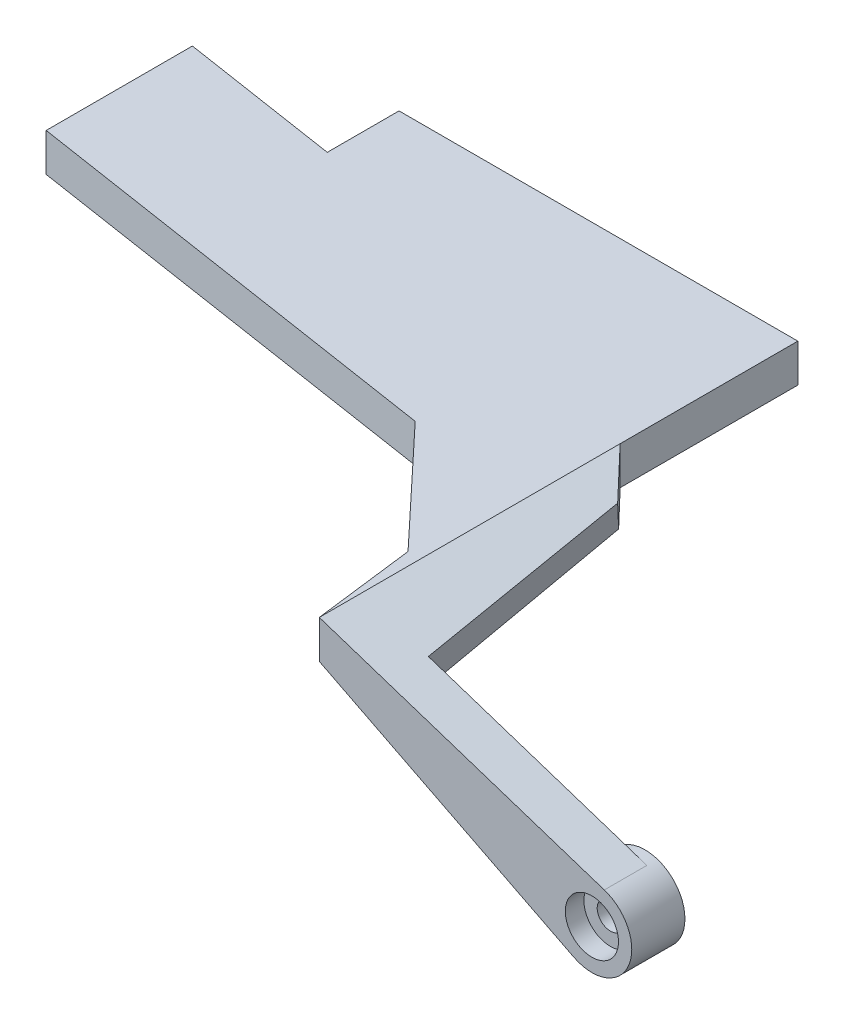
SolidWorks part; units mm, degrees
ref_plane "Alzado" through (0, 0, 0) normal (0, 0, 1) x (1, 0, 0)
ref_plane "Planta" through (0, 0, 0) normal (0, 1, 0) x (1, 0, 0)
ref_plane "Vista lateral" through (0, 0, 0) normal (1, 0, 0) x (0, 0, -1)
sketch "Croquis1" plane through (0, 0, 0) normal (0, 0, 1) x (1, 0, 0)
  circle A1 centre (10, 0) radius 2.5
  circle A2 centre (10, 0) radius 5
  circle A3 centre (10, 0) radius 6
extrude "Saliente-Extruir1" add sketch "Croquis1" along normal blind 10 contours A3 A2 | A2 A1 | A1
sketch "Croquis2" plane through (0, 0, 10) normal (0, 0, 1) x (1, 0, 0)
  circle A0 centre (10, 0) radius 2.5
  circle A1 centre (10, 0) radius 5
extrude "Saliente-Extruir2" add sketch "Croquis2" against normal blind 7
sketch "Croquis3" plane through (0, 0, 10) normal (0, 0, 1) x (1, 0, 0)
  circle A0 centre (10, 0) radius 5
  dimension "D1" = 10
extrude "Cortar-Extruir2" cut sketch "Croquis3" against normal up to vertex (3.5 mm away)
sketch "Croquis4" plane through (0, 0, 0) normal (0, 0, -1) x (-1, 0, 0)
  circle A0 centre (-10, 0) radius 6
extrude "Cortar-Extruir3" cut sketch "Croquis4" against normal up to vertex (0.8 mm away)
sketch "Croquis5" plane through (0, 0, 10) normal (0, 0, 1) x (1, 0, 0)
  circle A0 centre (10, 0) radius 7.5
  circle A1 centre (10, 0) radius 5
  dimension "D1" = 15
  dimension "D2" = 10
extrude "Saliente-Extruir3" add sketch "Croquis5" against normal up to vertex (10 mm away)
sketch "Croquis6" plane through (0, 0, 10) normal (0, 0, 1) x (1, 0, 0)
  line L0 (-41.2676, -17.5483) -> (6.6124, 6.6914)
  line L1 (-41.2676, -24.7171) -> (12.3385, -7.1261)
  line L2 (-41.2676, -17.5483) -> (-41.2676, -24.7171)
  circle A0 centre (10, 0) radius 7.5 construction
  arc A1 (6.6124, 6.6914) -> (12.3385, -7.1261) centre (10, 0) ccw
extrude "Saliente-Extruir4" add sketch "Croquis6" against normal blind 8
sketch "Croquis7" plane through (0, 0, 10) normal (0, 0, 1) x (1, 0, 0)
  line L0 (-41.2676, -24.7171) -> (-116.2676, -24.7171)
  line L1 (-41.2676, -24.7171) -> (-41.2676, -17.5483)
  line L4 (-41.2676, -17.5483) -> (-116.2676, -17.5483)
  line L5 (-116.2676, -17.5483) -> (-116.2676, -24.7171)
  dimension "D1" = 75
extrude "Saliente-Extruir5" add sketch "Croquis7" against normal blind 90 contours L5 L0 L1 L4
sketch "Croquis8" plane through (0, -24.7171, 0) normal (0, -1, 0) x (1, 0, 0)
  line L0 (-27.9791, 2) -> (-41.2676, -39)
  line L1 (-41.2676, 2) -> (12.3385, 2) construction
  line L2 (-41.2676, -80) -> (-41.2676, 2) construction
  line L3 (-41.2676, -39) -> (-41.2676, 2)
  line L4 (-41.2676, 2) -> (-27.9791, 2)
extrude "Saliente-Extruir6" add sketch "Croquis8" against normal up to vertex
sketch "Croquis10" plane through (0, 0, 2) normal (0, 0, -1) x (-1, 0, 0)
  line L0 (41.2676, -17.5483) -> (27.9791, -17.5483)
  line L1 (27.9791, -17.5483) -> (27.9791, -10.8209)
  line L2 (-6.6124, 6.6914) -> (41.2676, -17.5483) construction
  line L3 (27.9791, -10.8209) -> (41.2676, -17.5483)
extrude "Saliente-Extruir9" add sketch "Croquis10" along normal up to vertex (41 mm away)
sketch "Croquis11" plane through (0, 0, -39) normal (0, 0, -1) x (-1, 0, 0)
  line L0 (41.2676, -17.5483) -> (41.2676, -24.7171)
  line L1 (41.2676, -24.7171) -> (27.9791, -20.3564)
  line L2 (27.9791, -20.3564) -> (27.9791, -17.5483)
  line L3 (27.9791, -17.5483) -> (41.2676, -17.5483)
extrude "Saliente-Extruir10" add sketch "Croquis11" against normal up to vertex (49 mm away)
sketch "Croquis12" plane through (0, 0, 2) normal (0, 0, 1) x (1, 0, 0)
  line L0 (-41.2676, -24.7171) -> (-27.9791, -20.3564)
  line L1 (-27.9791, -20.3564) -> (-27.9791, -24.7171)
  line L2 (-27.9791, -24.7171) -> (-41.2676, -24.7171)
extrude "Cortar-Extruir4" cut sketch "Croquis12" against normal up to vertex
sketch "Croquis13" plane through (-1.3475, 2.6616, 0) normal (-0.4517, 0.8922, 0) x (0.8922, 0.4517, 0)
  line L0 (-29.8501, -2) -> (-37.2972, 39)
  line L1 (-44.7444, 39) -> (-29.8501, 39) construction
  line L2 (-37.2972, 39) -> (-29.8501, 39)
  line L3 (-29.8501, 39) -> (-29.8501, -2)
extrude "Cortar-Extruir5" cut sketch "Croquis13" against normal through all
sketch "Croquis14" plane through (3.3106, -10.0886, 0) normal (0.3118, -0.9501, 0) x (0.9501, 0.3118, 0)
  line L0 (-29.9583, 2) -> (-32.9314, 2)
  line L1 (-32.9314, 2) -> (-36.108, -39)
  line L2 (-36.108, -39) -> (-29.9583, 2)
extrude "Cortar-Extruir7" cut sketch "Croquis14" against normal through all contours L2 L0 L1
sketch "Croquis15" plane through (3.3106, -10.0886, 0) normal (0.3118, -0.9501, 0) x (0.9501, 0.3118, 0)
  line L0 (-26.1664, 2) -> (-33.7454, 2)
  line L1 (-32.9314, 2) -> (9.5015, 2) construction
  line L2 (-33.7454, 2) -> (-39.4297, -39)
  line L3 (-36.108, -39) -> (-46.917, -39) construction
  line L4 (-39.4297, -39) -> (-33.7454, -39)
  line L5 (-33.7454, -39) -> (-26.1664, 2)
extrude "Cortar-Extruir8" cut sketch "Croquis15" against normal through all
sketch "Croquis16" plane through (0, -17.5483, 0) normal (0, 1, 0) x (1, 0, 0)
  line L0 (-41.2676, -10) -> (-46.0414, 28.1515)
  line L1 (-46.0414, 28.1515) -> (-116.2676, 39)
  line L2 (-116.2676, 80) -> (-116.2676, -10) construction
  line L3 (-116.2676, 39) -> (-116.2676, -10)
  line L4 (-116.2676, -10) -> (-41.2676, -10)
extrude "Cortar-Extruir9" cut sketch "Croquis16" against normal through all
sketch "Croquis17" plane through (0, -24.7171, 0) normal (0, -1, 0) x (1, 0, 0)
  line L0 (-116.2676, -39) -> (-116.2676, -59.5)
  line L2 (-116.2676, -80) -> (-116.2676, -39) construction
  line L3 (-116.2676, -59.5) -> (-146.2676, -59.5)
  line L4 (-146.2676, -59.5) -> (-146.2676, -39)
  line L5 (-146.2676, -39) -> (-116.2676, -39)
  dimension "D1" = 20.5
  dimension "D2" = 30
extrude "Saliente-Extruir12" add sketch "Croquis17" against normal up to vertex
sketch "Croquis18" plane through (0, -24.7171, 0) normal (0, -1, 0) x (1, 0, 0)
  line L0 (-146.2676, -59.5) -> (-116.2676, -59.5)
  line L1 (-116.2676, -59.5) -> (-146.2676, -64.1442)
  line L2 (-146.2676, -64.1442) -> (-146.2676, -59.5)
  line L4 (-116.2676, -39) -> (-146.2676, -43.6344)
  line L5 (-146.2676, -39) -> (-146.2676, -59.5) construction
  line L6 (-146.2676, -43.6344) -> (-146.2676, -39)
  line L7 (-146.2676, -39) -> (-116.2676, -39)
  dimension "D1" = 8.8
extrude "Cortar-Extruir10" cut sketch "Croquis18" against normal through all contours L2 L0 L1 | L7 L4 L6
sketch "Croquis19" plane through (0, -24.7171, 0) normal (0, -1, 0) x (1, 0, 0)
  line L0 (-146.2676, -59.5) -> (-116.2676, -59.5)
  line L1 (-116.2676, -59.5) -> (-146.2676, -64.1344)
  line L2 (-146.2676, -64.1344) -> (-146.2676, -59.5)
extrude "Saliente-Extruir13" add sketch "Croquis19" against normal up to vertex
sketch "Croquis20" plane through (0, -24.7171, 0) normal (0, -1, 0) x (1, 0, 0)
  line L0 (-146.2676, -64.1344) -> (-116.2676, -59.5)
  line L1 (-116.2676, -59.5) -> (-116.2676, -66.5)
  line L2 (-116.2676, -80) -> (-116.2676, -59.5) construction
  line L3 (-146.2676, -64.1344) -> (-146.2676, -71.1344)
  line L4 (-146.2676, -71.1344) -> (-116.2676, -66.5)
  dimension "D2" = 7
  dimension "D1" = 7
extrude "Saliente-Extruir14" add sketch "Croquis20" against normal up to vertex
mirror "Simetría5" about plane through (-41.2676, -24.7171, -80) normal (0, 1, 0) of bodies 122
sketch "Croquis22" plane through (3.1743, 0, -20.5486) normal (-0.1527, 0, 0.9883) x (0.9883, 0, 0.1527)
  line L0 (-151.2146, -24.7171) -> (-160.9294, -24.7171)
  line L1 (-151.2146, -31.8858) -> (-151.2146, -17.5483) construction
  line L2 (-160.9294, -24.7171) -> (-160.9294, 29.1518)
  line L3 (-160.9294, 29.1518) -> (25.9068, 29.1518)
  line L4 (25.9068, 29.1518) -> (25.9068, -24.7171)
  line L5 (25.9068, -24.7171) -> (-151.2146, -24.7171)
extrude "Cortar-Extruir12" cut sketch "Croquis22" against normal through all and the other way through all
sketch "Croquis25" plane through (0, -31.8858, 0) normal (0, -1, 0) x (1, 0, 0)
  line L2 (-41.2676, 10) -> (-46.0414, -28.1515) construction
  line L3 (-43.6545, -9.0757) -> (-64.1814, -30.9537)
  line L4 (-46.0414, -28.1515) -> (-146.2676, -43.6344) construction
  line L5 (-64.1814, -30.9537) -> (-46.0414, -28.1515)
  line L6 (-46.0414, -28.1515) -> (-43.6545, -9.0757)
  dimension "D2" = 30
extrude "Saliente-Extruir15" add sketch "Croquis25" against normal up to vertex
sketch "Croquis26" plane through (0, -31.8858, 0) normal (0, -1, 0) x (1, 0, 0)
  line L0 (-34.1535, -39) -> (-41.2676, -46.5823)
  line L1 (-41.2676, -80) -> (-41.2676, -39) construction
  line L2 (-41.2676, -46.5823) -> (-41.2676, -39)
  line L3 (-41.2676, -39) -> (-34.1535, -39)
extrude "Saliente-Extruir16" add sketch "Croquis26" against normal up to vertex
sketch "Croquis27" plane through (0, -31.8858, 0) normal (0, -1, 0) x (1, 0, 0)
  line L0 (-41.2676, -39) -> (-34.1535, -39)
  line L1 (-34.1535, -39) -> (-41.2676, -46.5823)
  line L2 (-41.2676, -46.5823) -> (-41.2676, -39)
extrude "Saliente-Extruir17" add sketch "Croquis27" along normal up to vertex
sketch "Croquis28" plane through (0, 0, -39) normal (0, 0, 1) x (1, 0, 0)
  line L0 (-41.2676, -31.8858) -> (-41.2676, -34.2856)
  line L1 (-41.2676, -34.2856) -> (-36.5274, -34.2856)
  line L2 (-36.5274, -34.2856) -> (-41.2676, -31.8858)
  line L3 (-41.2676, -24.7171) -> (-34.1535, -24.7171)
  line L4 (-34.1535, -24.7171) -> (-34.1535, -27.0516)
  line L5 (-34.1535, -27.0516) -> (-41.2676, -24.7171)
  line L6 (-34.1535, -27.0516) -> (-36.5274, -34.2856)
  line L7 (-34.1535, -34.2856) -> (-34.1535, -27.0516)
extrude "Cortar-Extruir13" cut sketch "Croquis28" against normal through all contours L5 L3 L4 | L2 L0 L1
sketch "Croquis29" plane through (0, 0, -39) normal (0, 0, 1) x (1, 0, 0)
  line L0 (-34.1535, -27.0516) -> (-36.5274, -34.2856)
  line L1 (-36.5274, -34.2856) -> (-34.1535, -34.2856)
  line L2 (-34.1535, -34.2856) -> (-34.1535, -27.0516)
extrude "Cortar-Extruir14" cut sketch "Croquis29" against normal through all
sketch "Croquis30" plane through (-21.2683, -42.0106, 0) normal (-0.4517, -0.8922, 0) x (0.8922, -0.4517, 0)
  line L0 (-17.1031, -39) -> (-17.1031, -41.5301)
  line L1 (-17.1031, -39) -> (-17.5126, -41.9195)
  line L3 (-22.4162, -46.5823) -> (-17.1031, -41.5301) construction
  line L4 (-17.5126, -41.9195) -> (-17.1031, -41.5301)
extrude "Cortar-Extruir15" cut sketch "Croquis30" against normal through all
sketch "Croquis33" plane through (-11.3343, -34.5397, 0) normal (0.3118, 0.9501, 0) x (0.9501, -0.3118, 0)
  line L0 (-24.0165, 39) -> (-24.4212, 41.9195)
  line L1 (-24.4212, 41.9195) -> (-24.0165, 40.9333)
  line L2 (-24.0165, 40.9333) -> (-24.0165, 39)
extrude "Cortar-Extruir16" cut sketch "Croquis33" against normal through all
